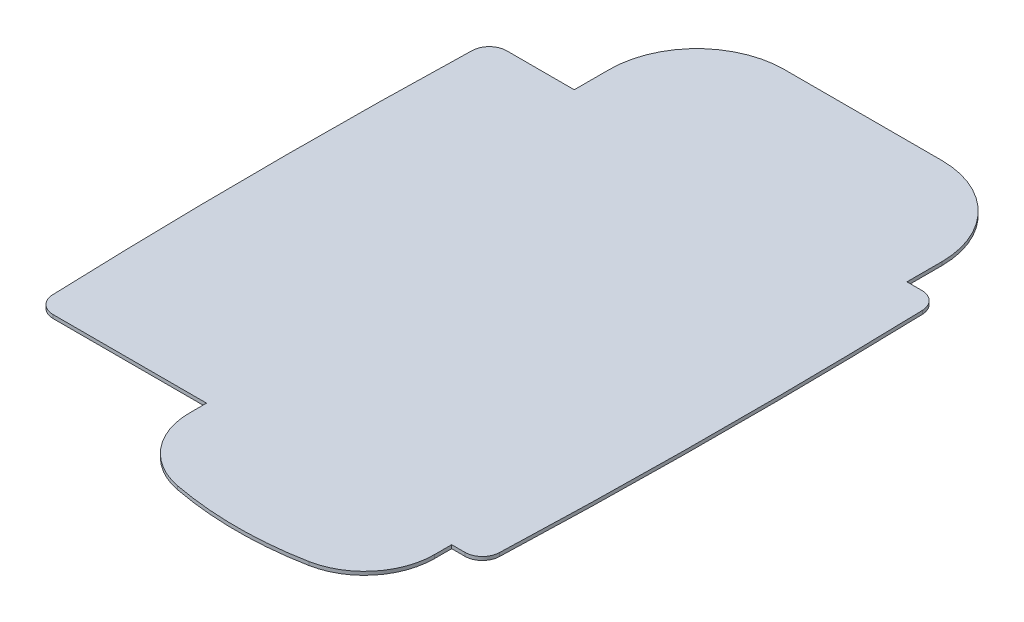
SolidWorks part; units mm, degrees
ref_plane "正面" through (0, 0, 0) normal (0, 0, 1) x (1, 0, 0)
ref_plane "平面" through (0, 0, 0) normal (0, 1, 0) x (1, 0, 0)
ref_plane "右側面" through (0, 0, 0) normal (1, 0, 0) x (0, 0, -1)
sketch "ｽｹｯﾁ1" plane through (0, 0, 0) normal (0, 1, 0) x (1, 0, 0)
  line L1 (-65, 92.5) -> (65, 92.5)
  line L2 (-65, 92.5) -> (-65, -92.5) construction
  line L3 (-65, -92.5) -> (65, -92.5)
  line L4 (65, 92.5) -> (65, -92.5) construction
  ellipse E0 centre (0, 0) end of major axis (0, -350) minor radius 65
  point P11 (-65, 0)
  dimension "D1" = 130
  dimension "D2" = 700
  dimension "D3" = 185
extrude "ﾎﾞｽ - 押し出し1" add sketch "ｽｹｯﾁ1" along normal mid plane 1 contours L3 E0 L1
sketch "ｽｹｯﾁ3" plane through (0, 0.5, 0) normal (0, 1, 0) x (1, 0, 0)
  line L0 (-62.6889, 92.5) -> (62.6889, 92.5) construction
  line L1 (-65, 92.5) -> (-40, 92.5)
  line L2 (-65, 92.5) -> (-65, 57.5)
  line L3 (-65, 57.5) -> (-40, 57.5)
  line L4 (-40, 92.5) -> (-40, 57.5)
  ellipse E0 centre (0, 0) end of major axis (0, -350) minor radius 65 (-62.6889, 92.5) -> (-62.6889, -92.5) ccw construction
  dimension "D1" = 35
  dimension "D2" = 25
extrude "ｶｯﾄ - 押し出し1" cut sketch "ｽｹｯﾁ3" against normal through all
sketch "ｽｹｯﾁ4" plane through (0, 0.5, 0) normal (0, 1, 0) x (1, 0, 0)
  line L0 (-40, 92.5) -> (62.6889, 92.5) construction
  line L1 (55, 92.5) -> (65, 92.5)
  line L2 (55, 92.5) -> (55, 57.5)
  line L3 (55, 57.5) -> (65, 57.5)
  line L4 (65, 92.5) -> (65, 57.5)
  line L5 (-64.1168, 57.5) -> (-40, 57.5) construction
  ellipse E0 centre (0, 0) end of major axis (0, -350) minor radius 65 (62.6889, -92.5) -> (62.6889, 92.5) ccw construction
  dimension "D1" = 10
extrude "ｶｯﾄ - 押し出し2" cut sketch "ｽｹｯﾁ4" against normal through all
sketch "ｽｹｯﾁ5" plane through (0, 0.5, 0) normal (0, 1, 0) x (1, 0, 0)
  line L0 (-62.6889, -92.5) -> (62.6889, -92.5) construction
  line L1 (-65, -72.5) -> (-15, -72.5)
  line L2 (-65, -72.5) -> (-65, -92.5)
  line L3 (-65, -92.5) -> (-15, -92.5)
  line L4 (-15, -72.5) -> (-15, -92.5)
  ellipse E0 centre (0, 0) end of major axis (0, -350) minor radius 65 (-64.1168, 57.5) -> (-62.6889, -92.5) ccw construction
  point P11 (0, 0)
  dimension "D1" = 20
  dimension "D2" = 50
extrude "ｶｯﾄ - 押し出し3" cut sketch "ｽｹｯﾁ5" against normal through all
sketch "ｽｹｯﾁ6" plane through (0, 0.5, 0) normal (0, 1, 0) x (1, 0, 0)
  line L0 (-15, -92.5) -> (62.6889, -92.5) construction
  line L1 (55, -72.5) -> (65, -72.5)
  line L2 (55, -72.5) -> (55, -92.5)
  line L3 (55, -92.5) -> (65, -92.5)
  line L4 (65, -72.5) -> (65, -92.5)
  line L7 (-15, -72.5) -> (-63.5902, -72.5) construction
  line L8 (55, 92.5) -> (55, 57.5) construction
  ellipse E0 centre (0, 0) end of major axis (0, -350) minor radius 65 (62.6889, -92.5) -> (64.1168, 57.5) ccw construction
extrude "ｶｯﾄ - 押し出し4" cut sketch "ｽｹｯﾁ6" against normal through all
sketch "ｽｹｯﾁ7" plane through (0, 0, 0) normal (0, 1, 0) x (1, 0, 0)
  line L0 (-15, -92.5) -> (55, -92.5) construction
  line L1 (-15, -92.5) -> (55, -92.5)
  arc A0 (-15, -92.5) -> (55, -92.5) centre (20, 1.175) ccw
  dimension "D1" = 100
extrude "ﾎﾞｽ - 押し出し2" add sketch "ｽｹｯﾁ7" along normal mid plane 1
sketch "ｽｹｯﾁ8" plane through (0, 0.5, 0) normal (0, 1, 0) x (1, 0, 0)
  line L0 (-40, 92.5) -> (55, 92.5) construction
  line L1 (-40, 57.5) -> (-40, 92.5) construction
  line L2 (55, 92.5) -> (55, 57.5) construction
  line L3 (55, 92.5) -> (55, 57.5)
  line L4 (-40, 92.5) -> (55, 92.5)
  line L5 (-40, 57.5) -> (-40, 92.5)
  circle A0 centre (-15, 67.5) radius 25
  circle A1 centre (30, 67.5) radius 25
  line M6 (55, 92.5) -> (-40, 92.5)
  line M7 (-40, 92.5) -> (-40, 57.5)
  dimension "D1" = 45
extrude "ｶｯﾄ - 押し出し5" cut sketch "ｽｹｯﾁ8" against normal through all contours A0 L4 M7 | A1 L3 M6
sketch "ｽｹｯﾁ9" plane through (0, 0, 0) normal (0, 1, 0) x (1, 0, 0)
  line L0 (-64.1168, 57.5) -> (-40, 57.5) construction
  line L1 (-65, 57.5) -> (-20, 57.5)
  line L2 (-65, 57.5) -> (-65, 5.5)
  line L3 (-65, 5.5) -> (-20, 5.5)
  line L4 (-20, 57.5) -> (-20, 5.5)
  arc A0 (-15, 92.5) -> (-40, 67.5) centre (-15, 67.5) ccw construction
  arc A1 (-15, 92.5) -> (-40, 67.5) centre (-15, 67.5) ccw
  circle A2 centre (-15, 67.5) radius 20
  ellipse E0 centre (0, 0) end of major axis (0, -350) minor radius 65 (-64.1168, 57.5) -> (-63.5902, -72.5) ccw construction
  point P15 (0, 0)
  point P16 (0, 0)
  dimension "D1" = 40
  dimension "D2" = 52
  dimension "D3" = 45
fillet "ﾌｨﾚｯﾄ1" radius 5 4 edges at (-64.1168, 0, -57.5) (-63.5902, 0, 72.5) (63.5902, 0, 72.5) (64.1168, 0, -57.5)
fillet "ﾌｨﾚｯﾄ2" radius 20 2 edges at (-15, 0, 92.5) (55, 0, 92.5)
